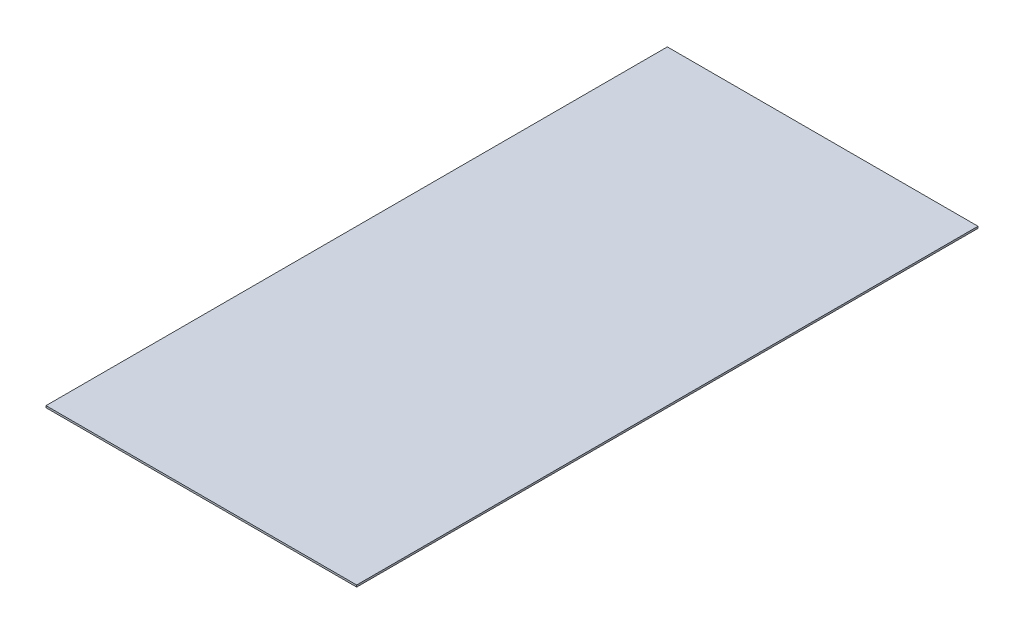
SolidWorks part; units mm, degrees
ref_plane "Ön Düzlem" through (0, 0, 0) normal (0, 0, 1) x (1, 0, 0)
ref_plane "Üst Düzlem" through (0, 0, 0) normal (0, 1, 0) x (1, 0, 0)
ref_plane "Sağ Düzlem" through (0, 0, 0) normal (1, 0, 0) x (0, 0, -1)
sketch "Çizim1" plane through (0, 0, 0) normal (0, 1, 0) x (1, 0, 0)
  line L1 (0, 0) -> (500, 0)
  line L2 (0, 0) -> (0, 1000)
  line L3 (0, 1000) -> (500, 1000)
  line L4 (500, 0) -> (500, 1000)
  dimension "D1" = 500
  dimension "D2" = 1000
extrude "Yükseklik-Ekstrüzyon1" add sketch "Çizim1" along normal blind 3
